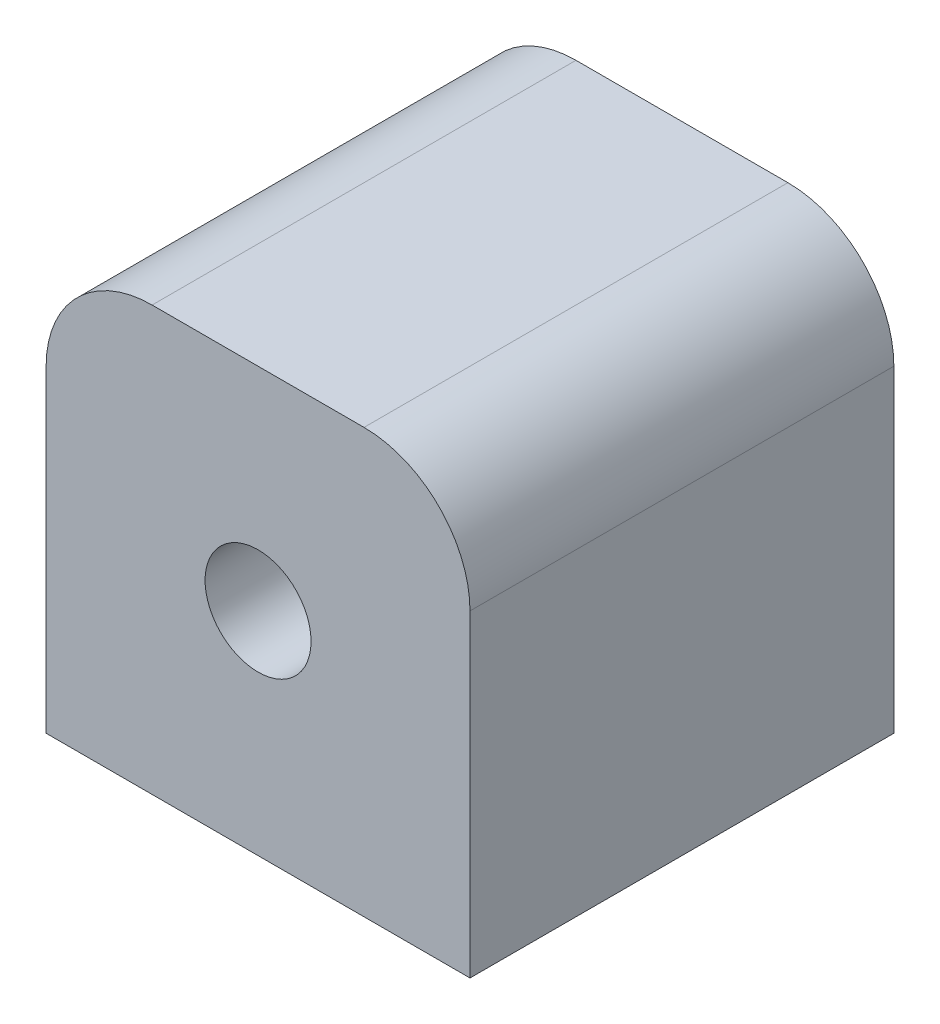
SolidWorks part; units mm, degrees
ref_plane "Front Plane" through (0, 0, 0) normal (0, 0, 1) x (1, 0, 0)
ref_plane "Top Plane" through (0, 0, 0) normal (0, 1, 0) x (1, 0, 0)
ref_plane "Right Plane" through (0, 0, 0) normal (1, 0, 0) x (0, 0, -1)
sketch "Sketch1" plane through (0, 0, 0) normal (0, 1, 0) x (1, 0, 0)
  line L1 (-20, 20) -> (20, 20)
  line L2 (-20, 20) -> (-20, -20)
  line L3 (-20, -20) -> (20, -20)
  line L4 (20, 20) -> (20, -20)
  line L5 (-20, 20) -> (20, -20) construction
  line L6 (-20, -20) -> (20, 20) construction
  point P0 (0, 0)
  dimension "D1" = 40
  dimension "D2" = 40
extrude "Boss-Extrude1" add sketch "Sketch1" along normal blind 40
sketch "Sketch2" plane through (0, 0, 20) normal (0, 0, 1) x (1, 0, 0)
  line L0 (-20, 40) -> (-20, 0) construction
  circle A0 centre (0, 20) radius 5
  point P7 (-20, 20)
  dimension "D1" = 10
extrude "Cut-Extrude1" cut sketch "Sketch2" against normal through all
fillet "Fillet1" radius 10 2 edges at (-20, 40, 0) (20, 40, 0)
hole_wizard "M6.5 Clearance Hole1" positions "Sketch4" profile "Sketch5" hole size "M6.5" standard "ANSI Metric"
sketch "Sketch4" plane through (0, 0, 0) normal (0, -1, 0) x (-1, 0, 0)
  line L0 (10, 10) -> (-10, 10) construction
  line L1 (-10, 10) -> (-10, -10) construction
  line L2 (-10, -10) -> (10, -10) construction
  line L3 (10, -10) -> (10, 10) construction
  point P0 (-10, 10)
  point P2 (10, 10)
  point P4 (-10, -10)
  point P6 (10, -10)
  point P16 (-10, 0)
  point P17 (0, -10)
  dimension "D1" = 20
sketch "Sketch5" plane through (10, 0, -10) normal (1, 0, 0) x (0, 0, -1)
  line L0 (0, 0) -> (0, 12.1331)
  line L1 (0, 12.1331) -> (3.55, 10)
  line L2 (3.55, 10) -> (3.55, 0.021)
  line L3 (3.55, 0.021) -> (3.575, 0)
  line L5 (3.575, 0) -> (0, 0)
  line L6 (-3.55, 0.021) -> (-3.575, 0) construction
  line L10 (0, 12.1331) -> (-3.55, 10) construction
  line L11 (0, -6.35) -> (0, 107.95) construction
  dimension "Hole Dia." = 7.1
  dimension "Hole Depth" = 10
  dimension "Near C'Sink Dia." = 7.15
  dimension "Near C'Sink Angle" = 100
  dimension "Drill Angle" = 118
sketch "Sketch6" plane through (0, 0, 0) normal (0, -1, 0) x (1, 0, 0)
  circle A0 centre (0, 0) radius 5
  dimension "D1" = 10
extrude "Cut-Extrude2" cut sketch "Sketch6" against normal blind 10
